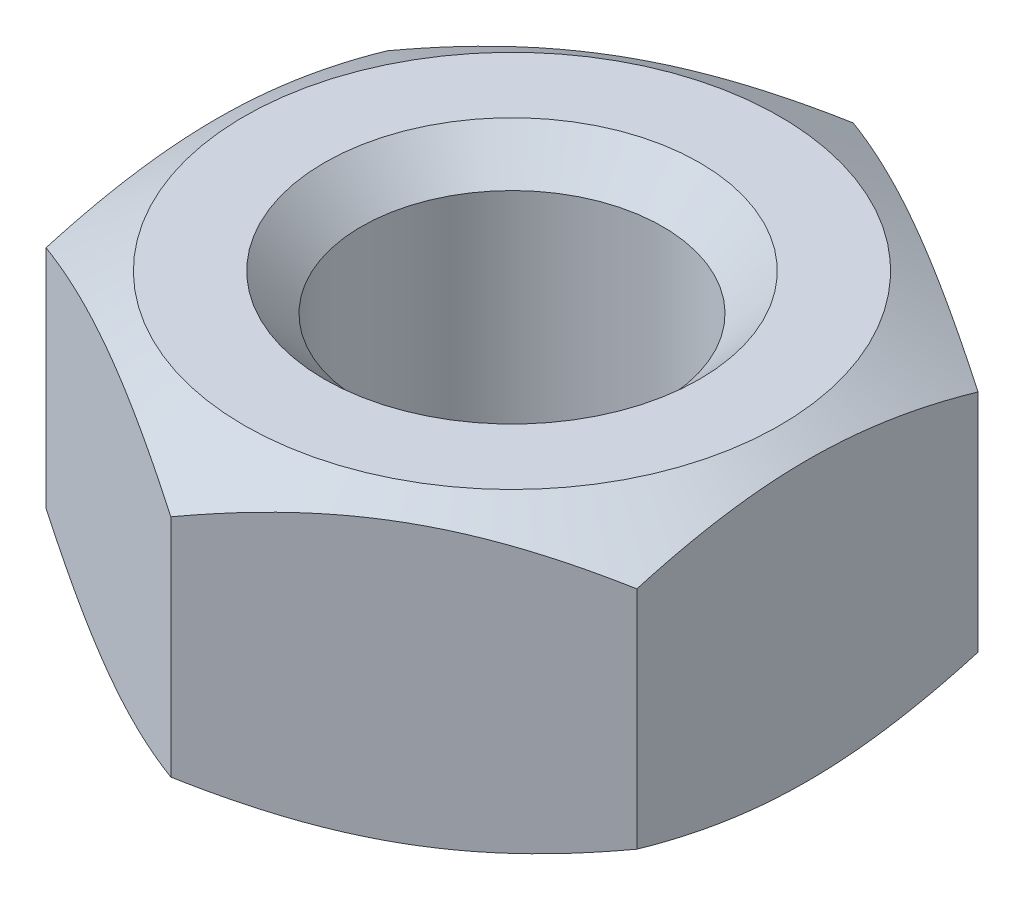
SolidWorks part; units mm, degrees
material "Простая углеродистая сталь"
ref_plane "Спереди" through (0, 0, 0) normal (0, 0, 1) x (1, 0, 0)
ref_plane "Сверху" through (0, 0, 0) normal (0, 1, 0) x (1, 0, 0)
ref_plane "Справа" through (0, 0, 0) normal (1, 0, 0) x (0, 0, -1)
sketch "Эскиз1" plane through (0, 0, 0) normal (0, 1, 0) x (1, 0, 0)
  line L1 (0, 9.2376) -> (-8, 4.6188)
  line L2 (-8, 4.6188) -> (-8, -4.6188)
  line L3 (-8, -4.6188) -> (0, -9.2376)
  line L4 (0, -9.2376) -> (8, -4.6188)
  line L5 (8, -4.6188) -> (8, 4.6188)
  line L6 (8, 4.6188) -> (0, 9.2376)
  circle A0 centre (0, 0) radius 8 construction
  dimension "S" = 16
extrude "Бобышка-Вытянуть1" add sketch "Эскиз1" along normal blind 8.4
hole_wizard "Отверстие обработанное метчиком M10x1.51" positions "Эскиз3" profile "Эскиз4" tap size "M10x1.5" standard "Ansi Metric" end condition through all
sketch "Эскиз3" plane through (0, 0, 0) normal (0, -1, 0) x (-1, 0, 0)
  point P0 (0, 0)
sketch "Эскиз4" plane through (0, 0, 0) normal (1, 0, 0) x (0, 0, -1)
  line L0 (0, 0) -> (0, 8.4)
  line L1 (0, 8.4) -> (4.08, 8.4)
  line L2 (4.08, 8.4) -> (4.08, 0)
  line L5 (4.08, 0) -> (0, 0)
  line L11 (0, -6.35) -> (0, 107.95) construction
  dimension "Диаметр проходного сверла" = 8.16
  dimension "Глубина проходного сверла" = 8.4
cosmetic thread "Отверстие резьбы1" parameters "D2"=10.715
cosmetic thread "Условное изображение резьбы1" [suppressed] parameters "D2"=3
chamfer "Фаска1" distance 1 angle 45 2 edges at (0, 0, -4.08) (0, 8.4, -4.08)
sketch "Эскиз5" plane through (0, 0, 0) normal (0, -1, 0) x (1, 0, 0)
  circle A0 centre (0, 0) radius 7.25
  dimension "dw" = 14.5
extrude "Вырез-Вытянуть1" cut sketch "Эскиз5" against normal through all draft 60 flip side to cut
sketch "Эскиз6" plane through (0, 8.4, 0) normal (0, 1, 0) x (1, 0, 0)
  circle A0 centre (0, 0) radius 7.25 construction
  circle A1 centre (0, 0) radius 7.25
extrude "Вырез-Вытянуть2" cut sketch "Эскиз6" against normal through all draft 60 flip side to cut
